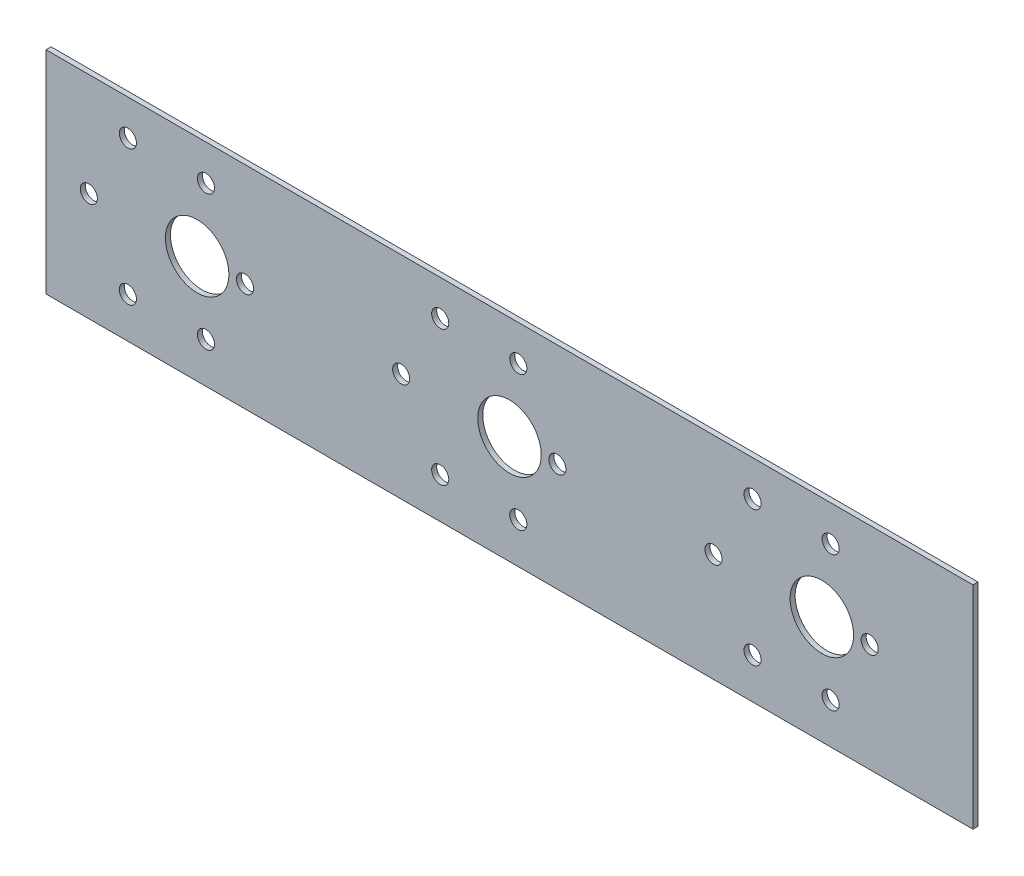
SolidWorks part; units mm, degrees
ref_plane "Front Plane" through (0, 0, 0) normal (0, 0, 1) x (1, 0, 0)
ref_plane "Top Plane" through (0, 0, 0) normal (0, 1, 0) x (1, 0, 0)
ref_plane "Right Plane" through (0, 0, 0) normal (1, 0, 0) x (0, 0, -1)
sketch "Boss bores and positive gearbox mounting holes profile" plane through (0, 0, 0) normal (0, 0, 1) x (1, 0, 0)
  line L0 (-92, 7) -> (92, 7)
  line L1 (92, 7) -> (92, 49)
  line L2 (92, 49) -> (-92, 49)
  line L3 (-92, 49) -> (-92, 7)
  circle A0 centre (-62, 28.5) radius 6.3
  circle A1 centre (0, 28.5) radius 6.3
  circle A2 centre (62, 28.5) radius 6.3
  circle A3 centre (-52.5, 28.5) radius 1.7
  circle A4 centre (-60.25, 41.9234) radius 1.7
  circle A5 centre (-75.75, 41.9234) radius 1.7
  circle A6 centre (-83.5, 28.5) radius 1.7
  circle A7 centre (-75.75, 15.0766) radius 1.7
  circle A8 centre (-60.25, 15.0766) radius 1.7
  circle A9 centre (9.5, 28.5) radius 1.7
  circle A10 centre (1.75, 41.9234) radius 1.7
  circle A11 centre (-13.75, 41.9234) radius 1.7
  circle A12 centre (-21.5, 28.5) radius 1.7
  circle A13 centre (-13.75, 15.0766) radius 1.7
  circle A14 centre (1.75, 15.0766) radius 1.7
  circle A15 centre (71.5, 28.5) radius 1.7
  circle A16 centre (63.75, 41.9234) radius 1.7
  circle A17 centre (48.25, 41.9234) radius 1.7
  circle A18 centre (40.5, 28.5) radius 1.7
  circle A19 centre (48.25, 15.0766) radius 1.7
  circle A20 centre (63.75, 15.0766) radius 1.7
extrude "Boss bores and positive gearbox mounting holes" add sketch "Boss bores and positive gearbox mounting holes profile" along normal blind 1
